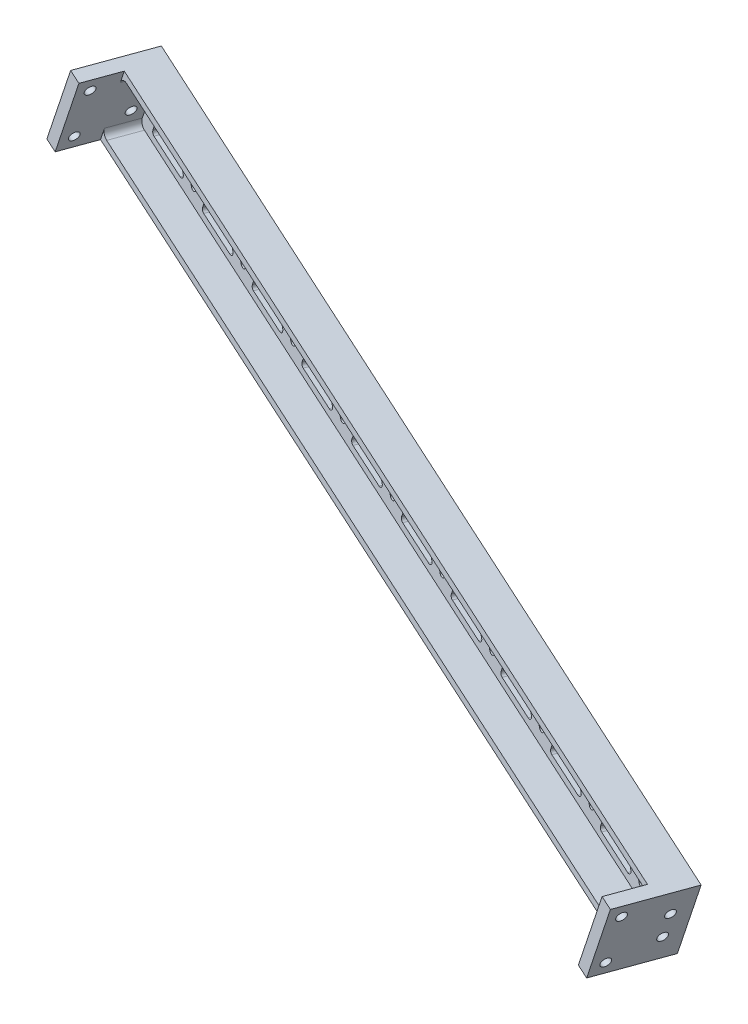
SolidWorks part; units mm, degrees
ref_plane "Front Plane" through (0, 0, 0) normal (0, 0, 1) x (1, 0, 0)
ref_plane "Top Plane" through (0, 0, 0) normal (0, 1, 0) x (1, 0, 0)
ref_plane "Right Plane" through (0, 0, 0) normal (1, 0, 0) x (0, 0, -1)
sketch3d "3DSketch1"
  line L0 (457.2, -152.4, 0) -> (457.2, -152.4, 127) construction
  line L1 (0, 0, 0) -> (38.3658, -12.7886, 10.6572)
  line L2 (0, 0, 0) -> (457.2, 0, 0) construction
  line L3 (457.2, 0, 0) -> (457.2, -152.4, 0) construction
  line L4 (38.3658, -12.7886, 10.6572) -> (407.1513, -135.7171, 113.0976)
  line L5 (407.1513, -135.7171, 113.0976) -> (457.2, -152.4, 127)
  line L6 (0, 0, 0) -> (457.2, -152.4, 127) construction
  dimension "D1" = 457.2
  dimension "D2" = 152.4
  dimension "D3" = 127
ref_plane "Plane1" through (38.3658, -12.7886, 10.6572) normal (0.9174, -0.3058, 0.2548) x (0.2417, -0.0806, -0.967)
ref_plane "Plane2" through (407.1513, -135.7171, 113.0976) normal (0.9174, -0.3058, 0.2548) x (0.2417, -0.0806, -0.967)
sketch "Sketch2" plane through (38.3658, -12.7886, 10.6572) normal (0.9174, -0.3058, 0.2548) x (0.2417, -0.0806, -0.967)
  line L1 (-19.05, 19.05) -> (19.05, 19.05)
  line L2 (-19.05, 19.05) -> (-19.05, -19.05)
  line L3 (-19.05, -19.05) -> (19.05, -19.05)
  line L4 (19.05, 19.05) -> (19.05, -19.05)
  line L5 (-19.05, 19.05) -> (19.05, -19.05) construction
  line L6 (-19.05, -19.05) -> (19.05, 19.05) construction
  point P0 (0, 0)
  dimension "D1" = 38.1
extrude "Boss-Extrude1" add sketch "Sketch2" along normal blind 6.35
sketch "Sketch3" plane through (44.191, -14.7303, 12.2753) normal (0.9174, -0.3058, 0.2548) x (0.2417, -0.0806, -0.967)
  line L0 (0, 19.05) -> (0, 15.875)
  line L1 (19.05, 19.05) -> (-19.05, 19.05) construction
  line L2 (0, 15.875) -> (15.875, 15.875)
  line L3 (15.875, 15.875) -> (15.875, -15.875)
  line L4 (15.875, -15.875) -> (0, -15.875)
  line L5 (0, -15.875) -> (0, -19.05)
  line L6 (-19.05, -19.05) -> (19.05, -19.05) construction
  line L7 (0, -19.05) -> (19.05, -19.05)
  line L8 (19.05, -19.05) -> (19.05, 19.05)
  line L9 (19.05, 19.05) -> (0, 19.05)
  dimension "D1" = 3.175
  dimension "D2" = 3.175
  dimension "D3" = 3.175
  dimension "D4" = 19.05
extrude "Boss-Extrude2" add sketch "Sketch3" along normal up to surface (407.1261 mm away)
sketch "Sketch4" plane through (417.6743, -139.2248, 116.0206) normal (0.9174, -0.3058, 0.2548) x (0.2417, -0.0806, -0.967)
  line L1 (-19.05, 19.05) -> (19.05, 19.05)
  line L2 (-19.05, 19.05) -> (-19.05, -19.05)
  line L3 (-19.05, -19.05) -> (19.05, -19.05)
  line L4 (19.05, 19.05) -> (19.05, -19.05)
  line L5 (-19.05, 19.05) -> (19.05, -19.05) construction
  line L6 (-19.05, -19.05) -> (19.05, 19.05) construction
  point P0 (0, 0)
extrude "Boss-Extrude3" add sketch "Sketch4" against normal blind 6.35
fillet "Fillet1" radius 3.175 4 edges at (408.7478, -152.983, 106.727) (418.788, -122.8623, 106.727) (41.0898, -30.4303, 4.5998) (51.13, -0.3096, 4.5998)
hole_wizard "#10-32 Tapped Hole1" positions "Sketch6" profile "Sketch7" tap size "#10-32" standard "ANSI Inch"
sketch "Sketch6" plane through (38.3658, -12.7886, 10.6572) normal (-0.9174, 0.3058, -0.2548) x (-0.2417, 0.0806, 0.967)
  line L0 (-19.05, 19.05) -> (19.05, 19.05) construction
  line L1 (19.05, 19.05) -> (19.05, -19.05) construction
  line L2 (19.05, -19.05) -> (-19.05, -19.05) construction
  line L3 (-19.05, -19.05) -> (-19.05, 19.05) construction
  point P0 (12.7, 12.7)
  point P2 (12.7, -12.7)
  point P4 (-9.525, -6.35)
  point P6 (-9.525, 6.35)
  dimension "D1" = 12.7
  dimension "D2" = 6.35
  dimension "D3" = 6.35
  dimension "D4" = 6.35
  dimension "D5" = 12.7
  dimension "D6" = 9.525
sketch "Sketch7" plane through (39.3117, 0.2831, 22.9379) normal (0.0393, 0.7066, 0.7066) x (-0.3961, -0.6382, 0.6602)
  line L0 (0, 0) -> (0, 6.35)
  line L1 (0, 6.35) -> (2.413, 6.35)
  line L2 (2.413, 6.35) -> (2.413, 0)
  line L5 (2.413, 0) -> (0, 0)
  line L11 (0, -6.35) -> (0, 107.95) construction
  dimension "Thread Major Dia." = 4.826
  dimension "Thru Tap Drill Depth" = 6.35
hole_wizard "#10-32 Tapped Hole2" positions "Sketch9" profile "Sketch10" tap size "#10-32" standard "ANSI Inch" end condition up to next
sketch "Sketch9" plane through (417.6743, -139.2248, 116.0206) normal (0.9174, -0.3058, 0.2548) x (0.2417, -0.0806, -0.967)
  line L0 (19.05, 19.05) -> (-19.05, 19.05) construction
  line L1 (-19.05, -19.05) -> (19.05, -19.05) construction
  line L2 (19.05, -19.05) -> (19.05, 19.05) construction
  line L3 (-19.05, 19.05) -> (-19.05, -19.05) construction
  point P0 (-12.7, 12.7)
  point P2 (-12.7, -12.7)
  point P4 (9.525, 6.35)
  point P6 (9.525, -6.35)
  dimension "D1" = 12.7
  dimension "D2" = 12.7
  dimension "D3" = 9.525
  dimension "D4" = 6.35
  dimension "D5" = 6.35
  dimension "D6" = 6.35
sketch "Sketch10" plane through (418.6202, -126.1531, 128.3014) normal (0.0393, 0.7066, 0.7066) x (0.3961, 0.6382, -0.6602)
  line L0 (0, 0) -> (0, 6.35)
  line L1 (0, 6.35) -> (2.413, 6.35)
  line L2 (2.413, 6.35) -> (2.413, 0)
  line L5 (2.413, 0) -> (0, 0)
  line L11 (0, -6.35) -> (0, 107.95) construction
  dimension "Thread Major Dia." = 4.826
  dimension "Thru Tap Drill Depth" = 6.35
sketch "Sketch11" plane through (3.8377, -1.2792, -15.3509) normal (-0.2417, 0.0806, 0.967) x (0.9703, 0.0201, 0.2409)
  line L0 (55.3955, -9.7161) -> (48.8842, -28.6052)
  line L1 (49.8677, -30.6234) -> (68.7568, -37.1348)
  line L2 (70.7013, -34.9385) -> (58.3235, -9.538)
  line L3 (72.3802, -38.3838) -> (78.3835, -40.4532) construction
  line L5 (49.6807, -3.6922) -> (41.403, -27.7055) construction
  line L6 (416.2629, -160.283) -> (43.3699, -31.7419) construction
  line L7 (79.6325, -36.8299) -> (86.1438, -17.9407)
  line L8 (85.1604, -15.9225) -> (66.2712, -9.4112)
  line L9 (64.3268, -11.6074) -> (76.7046, -37.0079)
  line L10 (426.61, -130.2664) -> (53.7171, -1.7253) construction
  line L11 (91.4155, -22.1326) -> (84.9042, -41.0218)
  line L12 (85.8877, -43.04) -> (104.7768, -49.5513)
  line L13 (106.7213, -47.3551) -> (94.3434, -21.9546)
  line L14 (115.6525, -49.2464) -> (122.1638, -30.3573)
  line L15 (121.1804, -28.3391) -> (102.2912, -21.8277)
  line L16 (100.3468, -24.024) -> (112.7246, -49.4245)
  line L17 (108.4001, -50.8003) -> (114.4035, -52.8698) construction
  line L18 (127.4355, -34.5492) -> (120.9242, -53.4384)
  line L19 (121.9076, -55.4565) -> (140.7968, -61.9679)
  line L20 (142.7412, -59.7716) -> (130.3634, -34.3711)
  line L21 (151.6725, -61.663) -> (158.1838, -42.7738)
  line L22 (157.2003, -40.7556) -> (138.3112, -34.2443)
  line L23 (136.3667, -36.4406) -> (148.7446, -61.8411)
  line L24 (144.4201, -63.2169) -> (150.4235, -65.2863) construction
  line L25 (163.4555, -46.9658) -> (156.9441, -65.8549)
  line L26 (157.9276, -67.8731) -> (176.8168, -74.3844)
  line L27 (178.7612, -72.1882) -> (166.3834, -46.7877)
  line L28 (187.6924, -74.0796) -> (194.2038, -55.1904)
  line L29 (193.2203, -53.1722) -> (174.3312, -46.6609)
  line L30 (172.3867, -48.8571) -> (184.7645, -74.2576)
  line L31 (180.4401, -75.6335) -> (186.4434, -77.7029) construction
  line L32 (199.4755, -59.3823) -> (192.9641, -78.2715)
  line L33 (193.9476, -80.2897) -> (212.8368, -86.801)
  line L34 (214.7812, -84.6048) -> (202.4034, -59.2043)
  line L35 (223.7124, -86.4961) -> (230.2238, -67.607)
  line L36 (229.2403, -65.5888) -> (210.3511, -59.0774)
  line L37 (208.4067, -61.2737) -> (220.7845, -86.6742)
  line L38 (216.4601, -88.05) -> (222.4634, -90.1194) construction
  line L39 (235.4954, -71.7989) -> (228.9841, -90.688)
  line L40 (229.9676, -92.7062) -> (248.8567, -99.2176)
  line L41 (250.8012, -97.0213) -> (238.4234, -71.6208)
  line L42 (259.7324, -98.9127) -> (266.2438, -80.0235)
  line L43 (265.2603, -78.0053) -> (246.3711, -71.494)
  line L44 (244.4267, -73.6902) -> (256.8045, -99.0907)
  line L45 (252.4801, -100.4666) -> (258.4834, -102.536) construction
  line L46 (271.5154, -84.2154) -> (265.0041, -103.1046)
  line L47 (265.9876, -105.1228) -> (284.8767, -111.6341)
  line L48 (286.8212, -109.4379) -> (274.4433, -84.0374)
  line L49 (295.7524, -111.3292) -> (302.2637, -92.4401)
  line L50 (301.2803, -90.4219) -> (282.3911, -83.9105)
  line L51 (280.4467, -86.1068) -> (292.8245, -111.5073)
  line L52 (288.5001, -112.8831) -> (294.5034, -114.9526) construction
  line L53 (307.5354, -96.632) -> (301.0241, -115.5212)
  line L54 (302.0075, -117.5394) -> (320.8967, -124.0507)
  line L55 (322.8411, -121.8544) -> (310.4633, -96.4539)
  line L56 (331.7724, -123.7458) -> (338.2837, -104.8566)
  line L57 (337.3002, -102.8385) -> (318.4111, -96.3271)
  line L58 (316.4666, -98.5234) -> (328.8445, -123.9239)
  line L59 (324.52, -125.2997) -> (330.5234, -127.3691) construction
  line L60 (343.5554, -109.0486) -> (337.044, -127.9377)
  line L61 (338.0275, -129.9559) -> (356.9167, -136.4673)
  line L62 (358.8611, -134.271) -> (346.4833, -108.8705)
  line L63 (367.7924, -136.1624) -> (374.3037, -117.2732)
  line L64 (373.3202, -115.255) -> (354.4311, -108.7437)
  line L65 (352.4866, -110.9399) -> (364.8644, -136.3404)
  line L66 (360.54, -137.7163) -> (366.5433, -139.7857) construction
  line L67 (379.5754, -121.4651) -> (373.064, -140.3543)
  line L68 (374.0475, -142.3725) -> (392.9367, -148.8838)
  line L69 (394.8811, -146.6876) -> (382.5033, -121.2871)
  line L70 (403.8123, -148.5789) -> (410.3237, -129.6898)
  line L71 (409.3402, -127.6716) -> (390.451, -121.1602)
  line L72 (388.5066, -123.3565) -> (400.8844, -148.757)
  line L73 (396.56, -150.1328) -> (402.5633, -152.2023) construction
  arc A0 (68.7568, -37.1348) -> (70.7013, -34.9385) centre (69.2742, -35.6339) ccw
  arc A1 (48.8842, -28.6052) -> (49.8677, -30.6234) centre (50.385, -29.1226) ccw
  arc A2 (55.3955, -9.7161) -> (58.3235, -9.538) centre (56.8964, -10.2334) cw
  arc A3 (79.6325, -36.8299) -> (76.7046, -37.0079) centre (78.1317, -36.3125) cw
  arc A4 (86.1438, -17.9407) -> (85.1604, -15.9225) centre (84.643, -17.4234) ccw
  arc A5 (66.2712, -9.4112) -> (64.3268, -11.6074) centre (65.7539, -10.912) ccw
  arc A6 (104.7768, -49.5513) -> (106.7213, -47.3551) centre (105.2942, -48.0505) ccw
  arc A7 (84.9042, -41.0218) -> (85.8877, -43.04) centre (86.405, -41.5392) ccw
  arc A8 (91.4155, -22.1326) -> (94.3434, -21.9546) centre (92.9164, -22.65) cw
  arc A9 (115.6525, -49.2464) -> (112.7246, -49.4245) centre (114.1517, -48.7291) cw
  arc A10 (122.1638, -30.3573) -> (121.1804, -28.3391) centre (120.663, -29.8399) ccw
  arc A11 (102.2912, -21.8277) -> (100.3468, -24.024) centre (101.7738, -23.3286) ccw
  arc A12 (140.7968, -61.9679) -> (142.7412, -59.7716) centre (141.3142, -60.4671) ccw
  arc A13 (120.9242, -53.4384) -> (121.9076, -55.4565) centre (122.425, -53.9557) ccw
  arc A14 (127.4355, -34.5492) -> (130.3634, -34.3711) centre (128.9363, -35.0666) cw
  arc A15 (151.6725, -61.663) -> (148.7446, -61.8411) centre (150.1716, -61.1456) cw
  arc A16 (158.1838, -42.7738) -> (157.2003, -40.7556) centre (156.683, -42.2565) ccw
  arc A17 (138.3112, -34.2443) -> (136.3667, -36.4406) centre (137.7938, -35.7451) ccw
  arc A18 (176.8168, -74.3844) -> (178.7612, -72.1882) centre (177.3341, -72.8836) ccw
  arc A19 (156.9441, -65.8549) -> (157.9276, -67.8731) centre (158.445, -66.3723) ccw
  arc A20 (163.4555, -46.9658) -> (166.3834, -46.7877) centre (164.9563, -47.4831) cw
  arc A21 (187.6924, -74.0796) -> (184.7645, -74.2576) centre (186.1916, -73.5622) cw
  arc A22 (194.2038, -55.1904) -> (193.2203, -53.1722) centre (192.703, -54.673) ccw
  arc A23 (174.3312, -46.6609) -> (172.3867, -48.8571) centre (173.8138, -48.1617) ccw
  arc A24 (212.8368, -86.801) -> (214.7812, -84.6048) centre (213.3541, -85.3002) ccw
  arc A25 (192.9641, -78.2715) -> (193.9476, -80.2897) centre (194.465, -78.7888) ccw
  arc A26 (199.4755, -59.3823) -> (202.4034, -59.2043) centre (200.9763, -59.8997) cw
  arc A27 (223.7124, -86.4961) -> (220.7845, -86.6742) centre (222.2116, -85.9788) cw
  arc A28 (230.2238, -67.607) -> (229.2403, -65.5888) centre (228.7229, -67.0896) ccw
  arc A29 (210.3511, -59.0774) -> (208.4067, -61.2737) centre (209.8338, -60.5783) ccw
  arc A30 (248.8567, -99.2176) -> (250.8012, -97.0213) centre (249.3741, -97.7167) ccw
  arc A31 (228.9841, -90.688) -> (229.9676, -92.7062) centre (230.4849, -91.2054) ccw
  arc A32 (235.4954, -71.7989) -> (238.4234, -71.6208) centre (236.9963, -72.3162) cw
  arc A33 (259.7324, -98.9127) -> (256.8045, -99.0907) centre (258.2316, -98.3953) cw
  arc A34 (266.2438, -80.0235) -> (265.2603, -78.0053) centre (264.7429, -79.5062) ccw
  arc A35 (246.3711, -71.494) -> (244.4267, -73.6902) centre (245.8538, -72.9948) ccw
  arc A36 (284.8767, -111.6341) -> (286.8212, -109.4379) centre (285.3941, -110.1333) ccw
  arc A37 (265.0041, -103.1046) -> (265.9876, -105.1228) centre (266.5049, -103.622) ccw
  arc A38 (271.5154, -84.2154) -> (274.4433, -84.0374) centre (273.0163, -84.7328) cw
  arc A39 (295.7524, -111.3292) -> (292.8245, -111.5073) centre (294.2516, -110.8119) cw
  arc A40 (302.2637, -92.4401) -> (301.2803, -90.4219) centre (300.7629, -91.9227) ccw
  arc A41 (282.3911, -83.9105) -> (280.4467, -86.1068) centre (281.8737, -85.4114) ccw
  arc A42 (320.8967, -124.0507) -> (322.8411, -121.8544) centre (321.4141, -122.5499) ccw
  arc A43 (301.0241, -115.5212) -> (302.0075, -117.5394) centre (302.5249, -116.0385) ccw
  arc A44 (307.5354, -96.632) -> (310.4633, -96.4539) centre (309.0362, -97.1494) cw
  arc A45 (331.7724, -123.7458) -> (328.8445, -123.9239) centre (330.2715, -123.2284) cw
  arc A46 (338.2837, -104.8566) -> (337.3002, -102.8385) centre (336.7829, -104.3393) ccw
  arc A47 (318.4111, -96.3271) -> (316.4666, -98.5234) centre (317.8937, -97.8279) ccw
  arc A48 (356.9167, -136.4673) -> (358.8611, -134.271) centre (357.434, -134.9664) ccw
  arc A49 (337.044, -127.9377) -> (338.0275, -129.9559) centre (338.5449, -128.4551) ccw
  arc A50 (343.5554, -109.0486) -> (346.4833, -108.8705) centre (345.0562, -109.5659) cw
  arc A51 (367.7924, -136.1624) -> (364.8644, -136.3404) centre (366.2915, -135.645) cw
  arc A52 (374.3037, -117.2732) -> (373.3202, -115.255) centre (372.8029, -116.7558) ccw
  arc A53 (354.4311, -108.7437) -> (352.4866, -110.9399) centre (353.9137, -110.2445) ccw
  arc A54 (392.9367, -148.8838) -> (394.8811, -146.6876) centre (393.454, -147.383) ccw
  arc A55 (373.064, -140.3543) -> (374.0475, -142.3725) centre (374.5649, -140.8716) ccw
  arc A56 (379.5754, -121.4651) -> (382.5033, -121.2871) centre (381.0762, -121.9825) cw
  arc A57 (403.8123, -148.5789) -> (400.8844, -148.757) centre (402.3115, -148.0616) cw
  arc A58 (410.3237, -129.6898) -> (409.3402, -127.6716) centre (408.8228, -129.1724) ccw
  arc A59 (390.451, -121.1602) -> (388.5066, -123.3565) centre (389.9337, -122.6611) ccw
  point P13 (48.3668, -30.1061)
  dimension "D5" = 1.5875
  dimension "D7" = 1.5875
  dimension "D1" = 6.35
  dimension "D2" = 25.4
  dimension "D3" = 7.366
  dimension "D4" = 3.175
  dimension "D6" = 3.175
  dimension "D8" = 10
extrude "Cut-Extrude1" cut sketch "Sketch11" against normal up to next contours L8 A5 L9 A3 L7 A4
